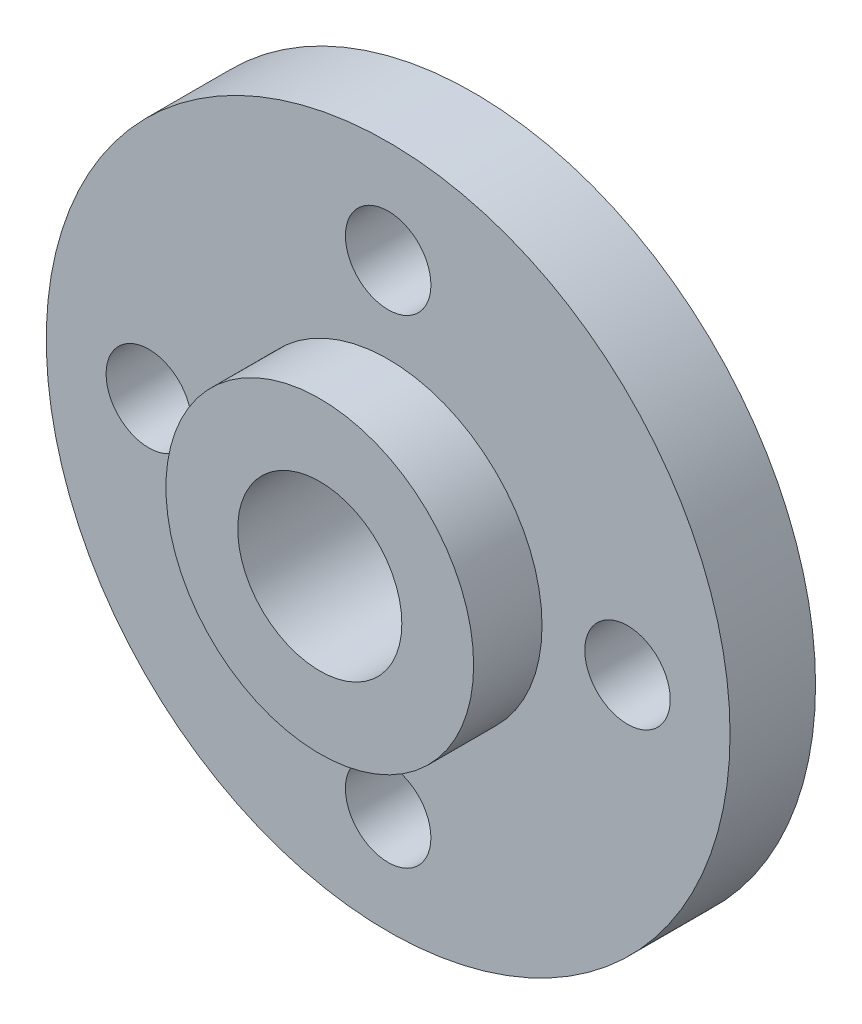
SolidWorks part; units mm, degrees
ref_plane "Alzado" through (0, 0, 0) normal (0, 0, 1) x (1, 0, 0)
ref_plane "Planta" through (0, 0, 0) normal (0, 1, 0) x (1, 0, 0)
ref_plane "Vista lateral" through (0, 0, 0) normal (1, 0, 0) x (0, 0, -1)
sketch "Croquis1" plane through (0, 0, 0) normal (0, 0, 1) x (1, 0, 0)
  circle A0 centre (0, 0) radius 10
  dimension "D1" = 20
extrude "Saliente-Extruir1" add sketch "Croquis1" along normal blind 2.5
sketch "Croquis2" plane through (0, 0, 2.5) normal (0, 0, 1) x (1, 0, 0)
  circle A0 centre (0, 0) radius 4.5
  dimension "D1" = 9
extrude "Saliente-Extruir2" add sketch "Croquis2" along normal blind 2
sketch "Croquis3" plane through (0, 0, 4.5) normal (0, 0, 1) x (1, 0, 0)
  circle A0 centre (0, 0) radius 2.4
  dimension "D1" = 4.8
extrude "Cortar-Extruir1" cut sketch "Croquis3" against normal through all
sketch "Croquis4" plane through (0, 0, 0) normal (0, 0, -1) x (-1, 0, 0)
  line L0 (0, 10) -> (0, -10) construction
  line L1 (-10, 0) -> (10, 0) construction
  circle A0 centre (0, 0) radius 10 construction
  circle A1 centre (0, 7) radius 1.25
  circle A2 centre (7, 0) radius 1.25
  circle A3 centre (0, -7) radius 1.25
  circle A4 centre (-7, 0) radius 1.25
  point P19 (0, 0)
  dimension "D1" = 2.5
  dimension "D2" = 7
  dimension "D3" = 4
extrude "Cortar-Extruir2" cut sketch "Croquis4" against normal through all
